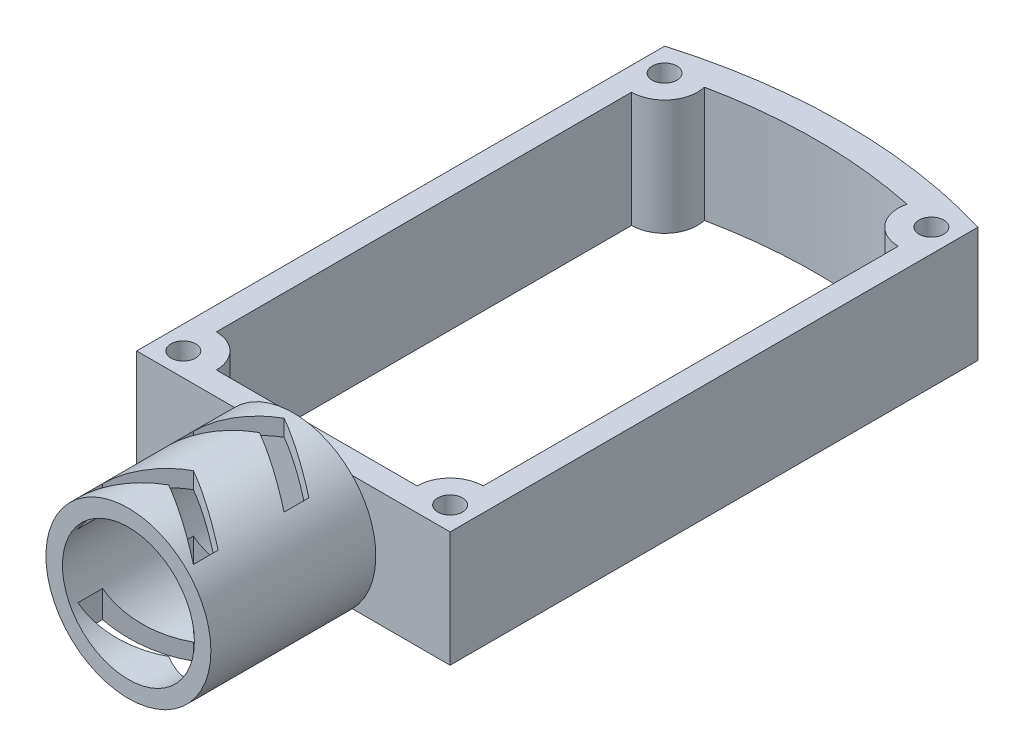
SolidWorks part; units mm, degrees
ref_plane "前视基准面" through (0, 0, 0) normal (0, 0, 1) x (1, 0, 0)
ref_plane "上视基准面" through (0, 0, 0) normal (0, 1, 0) x (1, 0, 0)
ref_plane "右视基准面" through (0, 0, 0) normal (1, 0, 0) x (0, 0, -1)
sketch "草图1" plane through (0, 0, 0) normal (0, 1, 0) x (1, 0, 0)
  line L0 (0, 0) -> (19, 0)
  line L1 (0, 0) -> (-19, 0)
  line L2 (-19, 0) -> (-19, 64)
  line L3 (19, 0) -> (19, 64)
  line L4 (-16.1716, 57.1716) -> (-16.1716, 6.8284)
  line L9 (-12.1716, 2.8284) -> (12.1716, 2.8284)
  line L10 (16.1716, 6.8284) -> (16.1716, 57.1716)
  arc A0 (-19, 64) -> (19, 64) centre (0, 0) cw
  circle A1 centre (-16.1716, 61.1716) radius 1.5
  circle A2 centre (16.1716, 61.1716) radius 1.5
  circle A3 centre (-16.1716, 2.8284) radius 1.5
  circle A4 centre (16.1716, 2.8284) radius 1.5
  arc A5 (-16.1716, 57.1716) -> (-12.2837, 62.1121) centre (-16.1716, 61.1716) ccw
  arc A6 (12.2837, 62.1121) -> (16.1716, 57.1716) centre (16.1716, 61.1716) ccw
  arc A8 (16.1716, 6.8284) -> (12.1716, 2.8284) centre (16.1716, 2.8284) ccw
  arc A9 (-12.1716, 2.8284) -> (-16.1716, 6.8284) centre (-16.1716, 2.8284) ccw
  arc A10 (12.2837, 62.1121) -> (-12.2837, 62.1121) centre (0, 2.8284) ccw
extrude "凸台-拉伸1" add sketch "草图1" along normal blind 14
sketch "草图2" plane through (0, 0, 0) normal (0, 0, 1) x (1, 0, 0)
  circle A0 centre (0, 7) radius 8
  circle A1 centre (0, 7) radius 10
extrude "凸台-拉伸2" add sketch "草图2" along normal blind 20
sketch "草图3" plane through (0, 0, 0) normal (0, 1, 0) x (1, 0, 0)
  line L0 (0, -1.1248) -> (7, -5.1248)
  line L1 (-7, -5.1248) -> (0, -1.1248)
  line L8 (-7, -5.1248) -> (-7, -8.1248)
  line L11 (0, -4.1248) -> (-7, -8.1248)
  line L12 (0, -4.1248) -> (7, -8.1248)
  line L13 (7, -5.1248) -> (7, -8.1248)
  line L14 (0, -12.1248) -> (7, -16.1248)
  line L15 (-7, -16.1248) -> (0, -12.1248)
  line L16 (-7, -16.1248) -> (-7, -19.1248)
  line L17 (0, -15.1248) -> (-7, -19.1248)
  line L18 (0, -15.1248) -> (7, -19.1248)
  line L19 (7, -16.1248) -> (7, -19.1248)
  dimension "D1" = 2
extrude "切除-拉伸4" cut sketch "草图3" against normal mid plane 40
sketch "草图6" plane through (0, 0, 0) normal (0, 1, 0) x (1, 0, 0)
  line L0 (0, -20) -> (0, -10)
  line L1 (-10, -20) -> (10, -20) construction
  circle A0 centre (0, -10) radius 1.5
extrude "切除-拉伸5" cut sketch "草图6" against normal blind 10
